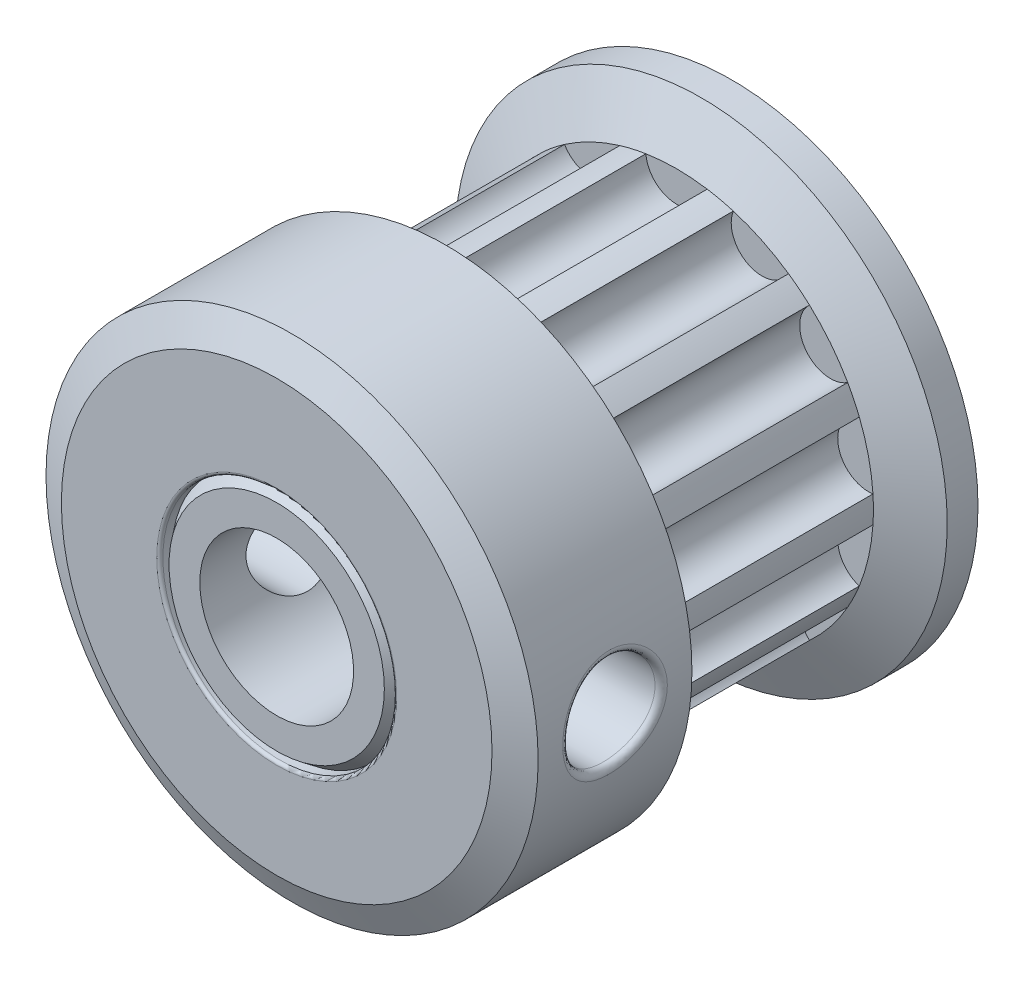
SolidWorks part; units mm, degrees
ref_plane "Plano frontal" through (0, 0, 0) normal (0, 0, 1) x (1, 0, 0)
ref_plane "Plano superior" through (0, 0, 0) normal (0, 1, 0) x (1, 0, 0)
ref_plane "Plano direito" through (0, 0, 0) normal (1, 0, 0) x (0, 0, -1)
sketch "Esboço1" plane through (0, 0, 0) normal (1, 0, 0) x (0, 0, -1)
  line L0 (0, 7) -> (0, 0) construction
  line L1 (0, 0) -> (14.8, 0) construction
  line L2 (0, 7) -> (0, 3.9)
  line L3 (0.1, 3.8) -> (0.4, 3.8)
  line L4 (0.4, 3.8) -> (0, 3.5)
  line L5 (0, 3.5) -> (0, 0)
  line L6 (0, 0) -> (14.8, 0)
  line L7 (14.8, 0) -> (14.8, 3.8543)
  line L8 (14.3, 4.3543) -> (13.9771, 4.3543)
  line L9 (13.9771, 4.3543) -> (13.9771, 6.3543)
  line L10 (0, 7) -> (0.5, 8)
  line L11 (0.5, 8) -> (5.5, 8)
  line L12 (5.5, 8) -> (6, 7)
  line L13 (6, 7) -> (6, 6.4)
  line L14 (6, 6.4) -> (13, 6.4)
  line L15 (13, 6.4) -> (13.8, 8)
  line L16 (13.8, 8) -> (14.8, 8)
  line L17 (14.8, 8) -> (13.9771, 6.3543)
  line L18 (14.8, 3.8543) -> (14.3, 4.3543)
  arc A0 (0, 3.9) -> (0.1, 3.8) centre (0.1, 3.9) ccw
  point P8 (14.8, 4.3543)
  point P23 (0, 3.8)
  dimension "D8" = 0.1
  dimension "D1" = 14.8
  dimension "D2" = 14.8
  dimension "D3" = 8
  dimension "D4" = 5
  dimension "D5" = 6
  dimension "D6" = 1
  dimension "D7" = 0.5
  dimension "D9" = 0.3
  dimension "D10" = 0.3
  dimension "D11" = 7
  dimension "D12" = 8
  dimension "D13" = 1
  dimension "D14" = 1.84
  dimension "D15" = 2
  dimension "D16" = 6.4
revolve "Revolução1" add sketch "Esboço1" angle 360 about L6
sketch "Esboço2" plane through (0, 0, -14.8) normal (0, 0, -1) x (-1, 0, 0)
  circle A0 centre (0, 0) radius 2.5
  dimension "D1" = 5
extrude "Corte-extrusão1" cut sketch "Esboço2" against normal through all contours A0
sketch "Esboço4" plane through (0, 0, -6) normal (0, 0, -1) x (-1, 0, 0)
  line L0 (0, 0) -> (0, 6.4) construction
  circle A5 centre (0, 0) radius 6.4 construction
  circle A6 centre (0, 6.4) radius 1
  circle A7 centre (2.7769, 5.7662) radius 1
  circle A8 centre (5.0037, 3.9903) radius 1
  circle A9 centre (6.2395, 1.4241) radius 1
  circle A10 centre (6.2395, -1.4241) radius 1
  circle A11 centre (5.0037, -3.9903) radius 1
  circle A12 centre (2.7769, -5.7662) radius 1
  circle A13 centre (0, -6.4) radius 1
  circle A14 centre (-2.7769, -5.7662) radius 1
  circle A15 centre (-5.0037, -3.9903) radius 1
  circle A16 centre (-6.2395, -1.4241) radius 1
  circle A17 centre (-6.2395, 1.4241) radius 1
  circle A18 centre (-5.0037, 3.9903) radius 1
  circle A19 centre (-2.7769, 5.7662) radius 1
  point P35 (0, 0)
  dimension "D1" = 2
  dimension "D2" = 14
extrude "Corte-extrusão2" cut sketch "Esboço4" along normal blind 7
sketch "Esboço5" plane through (0, 0, 0) normal (1, 0, 0) x (0, 0, -1)
  line L0 (0, 0) -> (6, 0) construction
  line L1 (6, -0.4348) -> (6, 0.4348) construction
  circle A0 centre (3, 0) radius 1.5
  dimension "D1" = 3
extrude "Corte-extrusão3" cut sketch "Esboço5" along normal through all and the other way through all contours A0
fillet "Filete1" radius 0.2 2 edges at (-7.9938, -0.3156, -4.4664) (7.9938, 0.3156, -4.4664)
